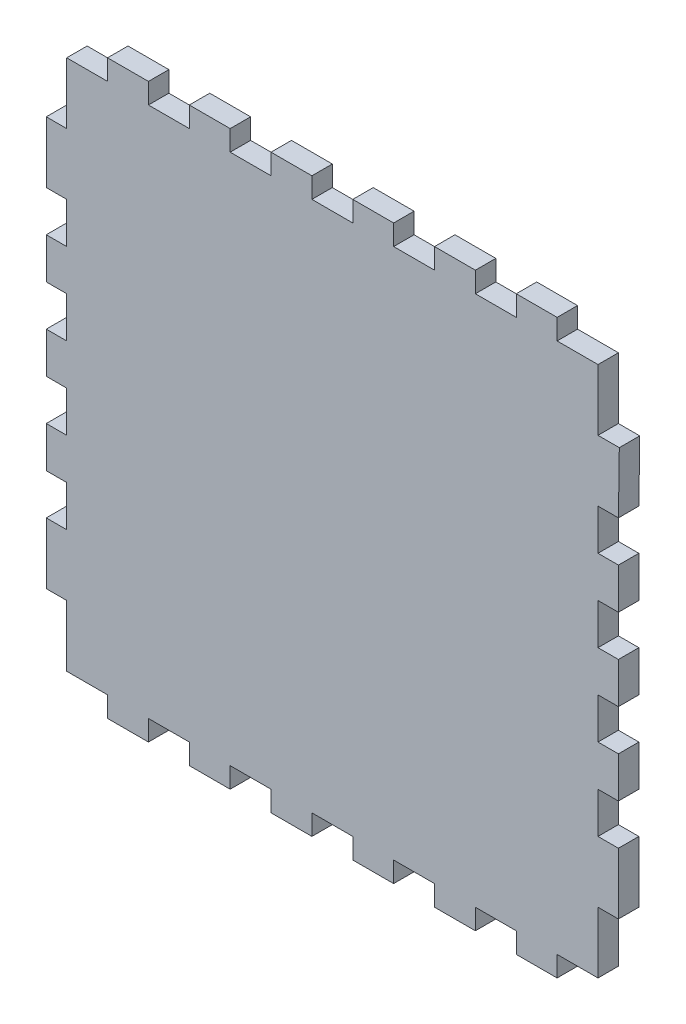
SolidWorks part; units mm, degrees
ref_plane "Front Plane" through (0, 0, 0) normal (0, 0, 1) x (1, 0, 0)
ref_plane "Top Plane" through (0, 0, 0) normal (0, 1, 0) x (1, 0, 0)
ref_plane "Right Plane" through (0, 0, 0) normal (1, 0, 0) x (0, 0, -1)
sketch "Sketch1" plane through (0, 0, 0) normal (0, 0, 1) x (1, 0, 0)
  line L0 (-44.809, -69.8705) -> (-34.809, -69.8705)
  line L1 (35.191, 60.1234) -> (45.191, 60.1234)
  line L2 (-44.809, 60.1234) -> (-34.809, 60.1234)
  line L3 (-54.809, 60.1234) -> (-64.809, 60.1234)
  line L4 (-64.809, -39.8705) -> (-64.809, -29.8705)
  line L5 (-54.809, 60.1234) -> (-54.809, 65.1234)
  line L6 (-64.809, -54.8705) -> (-64.809, -69.8705)
  line L7 (-54.809, 65.1234) -> (-44.809, 65.1234)
  line L8 (-54.809, -74.8705) -> (-54.809, -69.8705)
  line L9 (-64.809, 60.1234) -> (-64.809, 45.1234)
  line L10 (-44.809, 60.1234) -> (-44.809, 65.1234)
  line L11 (-44.809, -74.8705) -> (-44.809, -69.8705)
  line L12 (15.191, -69.8705) -> (25.191, -69.8705)
  line L13 (15.191, 60.1234) -> (25.191, 60.1234)
  line L14 (35.191, -74.8705) -> (35.191, -69.8705)
  line L15 (25.191, 65.1234) -> (35.191, 65.1234)
  line L16 (65.191, 60.1234) -> (65.191, 45.1234)
  line L17 (-69.809, 30.1234) -> (-64.809, 30.1295)
  line L18 (-34.809, -74.8705) -> (-34.809, -69.8705)
  line L19 (-64.809, 30.1295) -> (-64.809, 20.1295)
  line L20 (-69.809, 20.1295) -> (-64.809, 20.1295)
  line L21 (35.191, 60.1234) -> (35.191, 65.1234)
  line L22 (65.191, 30.1295) -> (70.191, 30.1295)
  line L23 (-24.809, -69.8705) -> (-24.809, -74.8705)
  line L24 (70.4072, 45.1234) -> (70.191, 30.1295)
  line L25 (45.191, 65.1234) -> (55.191, 65.1234)
  line L26 (55.191, 60.1234) -> (55.191, 65.1234)
  line L27 (-14.809, -69.8705) -> (-14.809, -74.8705)
  line L28 (45.191, 65.1234) -> (45.191, 60.1234)
  line L29 (55.191, -74.8705) -> (55.191, -69.8705)
  line L30 (45.191, -69.8705) -> (45.191, -74.8705)
  line L31 (45.191, -74.8705) -> (55.191, -74.8705)
  line L32 (-4.809, -69.8705) -> (-4.809, -74.8705)
  line L33 (55.191, 60.1234) -> (65.191, 60.1234)
  line L34 (35.191, -69.8705) -> (45.191, -69.8705)
  line L35 (-34.809, 60.1234) -> (-34.809, 65.1234)
  line L36 (5.191, -69.8705) -> (5.191, -74.8705)
  line L37 (55.191, -69.8705) -> (65.191, -69.8705)
  line L41 (15.191, -74.8705) -> (15.191, -69.8705)
  line L44 (25.191, -69.8705) -> (25.191, -74.8705)
  line L45 (-24.809, -69.8705) -> (-14.809, -69.8705)
  line L46 (-4.809, -69.8705) -> (5.191, -69.8705)
  line L48 (-54.809, -74.8705) -> (-44.809, -74.8705)
  line L49 (-34.809, -74.8705) -> (-24.809, -74.8705)
  line L50 (-14.809, -74.8705) -> (-4.809, -74.8705)
  line L51 (5.191, -74.8705) -> (15.191, -74.8705)
  line L52 (25.191, -74.8705) -> (35.191, -74.8705)
  line L54 (-54.809, -69.8705) -> (-64.809, -69.8705)
  line L55 (-34.809, 65.1234) -> (-24.809, 65.1234)
  line L57 (-24.809, 65.1234) -> (-24.809, 60.1234)
  line L60 (-24.809, 60.1234) -> (-14.809, 60.1234)
  line L61 (-14.809, 65.1234) -> (-14.809, 60.1234)
  line L63 (-14.809, 65.1234) -> (-4.809, 65.1234)
  line L66 (-4.809, 65.1234) -> (-4.809, 60.1234)
  line L69 (-4.809, 60.1234) -> (5.191, 60.1234)
  line L70 (5.191, 65.1234) -> (5.191, 60.1234)
  line L72 (5.191, 65.1234) -> (15.191, 65.1234)
  line L74 (15.191, 65.1234) -> (15.191, 60.1234)
  line L78 (25.191, 65.1234) -> (25.191, 60.1234)
  line L79 (-64.809, -54.8705) -> (-69.809, -54.8705)
  line L80 (-69.809, -54.8705) -> (-69.809, -39.8705)
  line L81 (-69.809, 0.1295) -> (-69.809, -9.8705)
  line L82 (-64.809, -39.8705) -> (-69.809, -39.8705)
  line L85 (-64.809, 45.1234) -> (-69.809, 45.1234)
  line L87 (-69.809, 45.1234) -> (-69.809, 30.1234)
  line L89 (-64.809, -29.8705) -> (-69.809, -29.8705)
  line L92 (-69.809, -29.8705) -> (-69.809, -19.8705)
  line L94 (-69.809, -19.8705) -> (-64.809, -19.8705)
  line L97 (-64.809, -19.8705) -> (-64.809, -9.8705)
  line L98 (-69.809, -9.8705) -> (-64.809, -9.8705)
  line L103 (-69.809, 0.1295) -> (-64.809, 0.1295)
  line L106 (-64.809, 0.1295) -> (-64.809, 10.1295)
  line L107 (-69.809, 10.1295) -> (-64.809, 10.1295)
  line L109 (-69.809, 10.1295) -> (-69.809, 20.1295)
  line L117 (70.191, -54.8705) -> (65.191, -54.8705)
  line L119 (70.191, -39.8705) -> (65.191, -39.8705)
  line L121 (70.4072, 45.1234) -> (65.191, 45.1234)
  line L123 (70.191, 20.1295) -> (70.191, 10.1295)
  line L125 (70.191, -29.8705) -> (65.191, -29.8705)
  line L130 (65.191, -19.8705) -> (70.191, -19.8705)
  line L134 (65.191, -9.8705) -> (70.191, -9.8705)
  line L136 (65.191, 0.1295) -> (70.191, 0.1295)
  line L143 (65.191, 10.1295) -> (70.191, 10.1295)
  line L148 (70.191, 20.1295) -> (65.191, 20.1295)
  line L152 (70.191, 0.1295) -> (70.191, -9.8705)
  line L153 (70.191, -19.8705) -> (70.191, -29.8705)
  line L154 (70.191, -54.8705) -> (70.191, -39.8705)
  line L155 (65.191, 30.1295) -> (65.191, 20.1295)
  line L156 (65.191, 10.1295) -> (65.191, 0.1295)
  line L158 (65.191, -9.8705) -> (65.191, -19.8705)
  line L159 (65.191, -29.8705) -> (65.191, -39.8705)
  line L160 (65.191, -54.8705) -> (65.191, -69.8705)
  point P0 (0, 0)
  dimension "D1" = 10
  dimension "D3" = 10
  dimension "D4" = 30
  dimension "D5" = 15
  dimension "D6" = 15
  dimension "D7" = 30
  dimension "D8" = 15
  dimension "D9" = 10
  dimension "D10" = 10
  dimension "D11" = 10
  dimension "D12" = 10
  dimension "D13" = 10
  dimension "D14" = 10
  dimension "D15" = 10
  dimension "D16" = 10
  dimension "D17" = 10
  dimension "D18" = 10
  dimension "D19" = 10
  dimension "D20" = 10
  dimension "D21" = 10
  dimension "D22" = 10
  dimension "D23" = 10
  dimension "D24" = 10
  dimension "D25" = 15
  dimension "D26" = 10
  dimension "D27" = 10
  dimension "D28" = 10
  dimension "D29" = 10
extrude "Boss-Extrude2" add sketch "Sketch1" along normal blind 5
